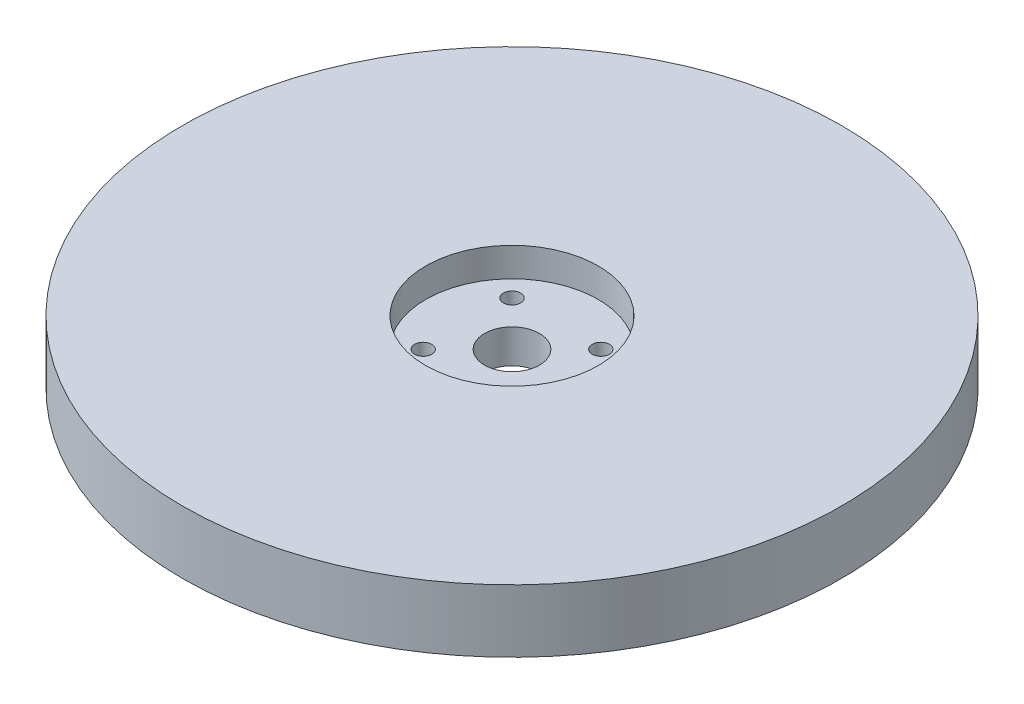
SolidWorks part; units mm, degrees
ref_plane "Piano frontale" through (0, 0, 0) normal (0, 0, 1) x (1, 0, 0)
ref_plane "Piano superiore" through (0, 0, 0) normal (0, 1, 0) x (1, 0, 0)
ref_plane "Piano destro" through (0, 0, 0) normal (1, 0, 0) x (0, 0, -1)
sketch "Schizzo1" plane through (0, 0, 0) normal (0, 1, 0) x (1, 0, 0)
  circle A0 centre (0, 0) radius 42
  dimension "D1" = 84
extrude "Estrusione-Estrusione1" add sketch "Schizzo1" along normal blind 8 contours A0
sketch "Schizzo2" plane through (0, 0, 0) normal (0, -1, 0) x (1, 0, 0)
  circle A0 centre (0, 0) radius 3.5
  dimension "D1" = 7
extrude "Taglio-Estrusione1" cut sketch "Schizzo2" against normal through all
sketch "Schizzo4" plane through (0, 8, 0) normal (0, 1, 0) x (1, 0, 0)
  circle A0 centre (0, 0) radius 11
  dimension "D1" = 22
extrude "Taglio-Estrusione2" cut sketch "Schizzo4" against normal blind 3.7
sketch "Schizzo5" plane through (0, 4.3, 0) normal (0, 1, 0) x (1, 0, 0)
  line L0 (0, -9.64) -> (0, 9.7177) construction
  line L1 (-10.0287, 0) -> (9.2512, 0) construction
  circle A1 centre (-5.66, 5.66) radius 1.1
  circle A2 centre (5.66, 5.66) radius 1.1
  circle A3 centre (5.66, -5.66) radius 1.1
  circle A4 centre (-5.66, -5.66) radius 1.1
  point P16 (0, 0)
  dimension "D1" = 2.2
  dimension "D2" = 5.66
  dimension "D3" = 5.66
  dimension "D5" = 11.32
  dimension "D6" = 5.66
  dimension "D4" = 4
extrude "Taglio-Estrusione3" cut sketch "Schizzo5" against normal blind 3
sketch "Schizzo6" plane through (0, 0, 0) normal (0, -1, 0) x (1, 0, 0)
  line L0 (0, -23.4779) -> (0, 22.545) construction
  line L1 (-37.4714, 0) -> (37.7046, 0) construction
  circle A0 centre (12, 12) radius 1.25
  circle A1 centre (12, -12) radius 1.25
  circle A2 centre (-24, 12) radius 1.25
  circle A3 centre (-24, -12) radius 1.25
  dimension "D1" = 2.5
  dimension "D2" = 12
  dimension "D4" = 2.5
  dimension "D5" = 12
  dimension "D6" = 24
  dimension "D3" = 12
extrude "Taglio-Estrusione4" cut sketch "Schizzo6" against normal blind 6
